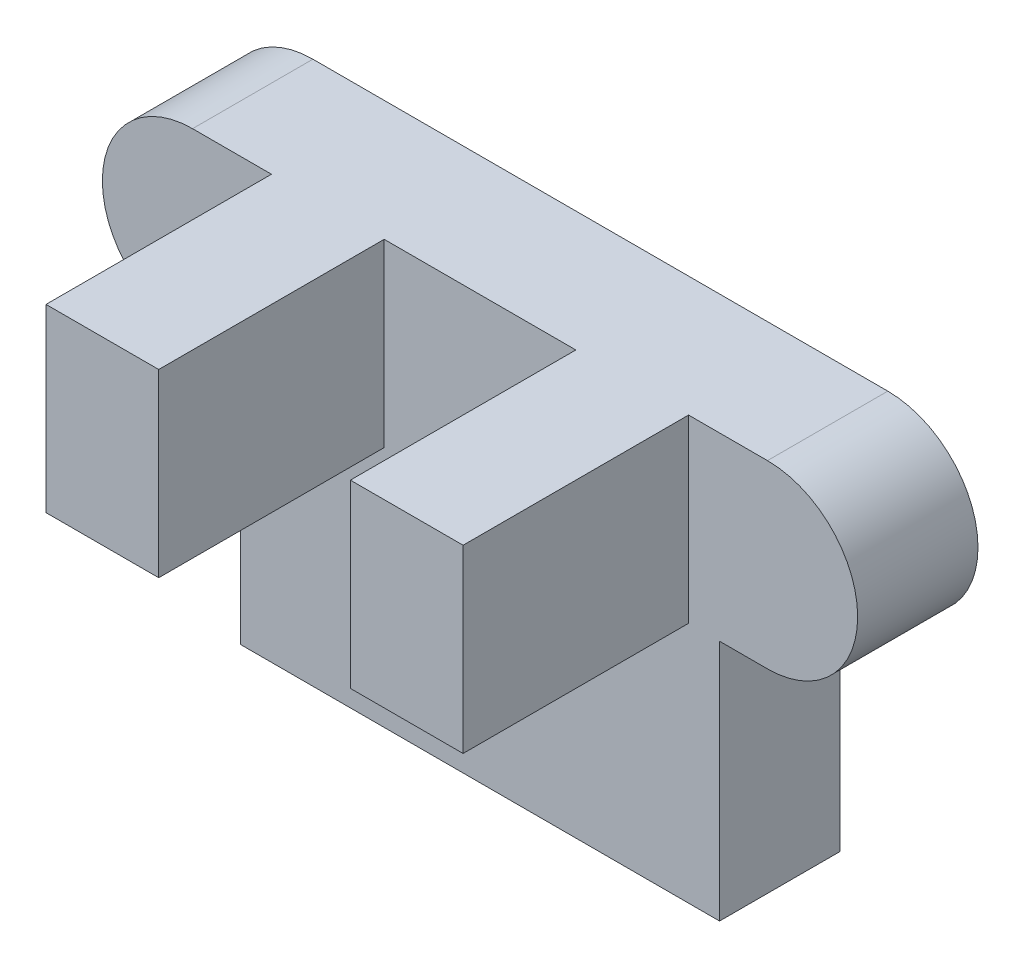
SolidWorks part; units mm, degrees
ref_plane "Front Plane" through (0, 0, 0) normal (0, 0, 1) x (1, 0, 0)
ref_plane "Top Plane" through (0, 0, 0) normal (0, 1, 0) x (1, 0, 0)
ref_plane "Right Plane" through (0, 0, 0) normal (1, 0, 0) x (0, 0, -1)
sketch "Sketch2" plane through (0, 0, 0) normal (0, 0, 1) x (1, 0, 0)
  line L0 (0, 0) -> (20.4, 0) construction
  line L1 (0, 3.2) -> (20.4, 3.2)
  line L2 (0, -3.2) -> (1.7, -3.2)
  line L3 (18.7, -3.2) -> (20.4, -3.2)
  line L5 (1.7, -3.2) -> (1.7, -11.8)
  line L6 (1.7, -11.8) -> (18.7, -11.8)
  line L7 (18.7, -3.2) -> (18.7, -11.8)
  arc A0 (0, 3.2) -> (0, -3.2) centre (0, 0) ccw
  arc A1 (20.4, -3.2) -> (20.4, 3.2) centre (20.4, 0) ccw
  point P3 (10.2, -11.8)
  point P12 (10.2, 3.2)
  point P13 (1.3211, -11.8)
  point P14 (0, 0)
  dimension "D5" = 3.2
  dimension "D1" = 20.4
  dimension "D2" = 6.4
  dimension "D3" = 17
  dimension "D4" = 8.6
extrude "Boss-Extrude1" add sketch "Sketch2" along normal blind 4.27
sketch "Sketch3" plane through (0, 0, 4.27) normal (0, 0, 1) x (1, 0, 0)
  line L0 (20.4, 3.2) -> (0, 3.2) construction
  line L1 (2.8, 3.2) -> (6.8, 3.2)
  line L2 (2.8, 3.2) -> (2.8, -3.2)
  line L3 (2.8, -3.2) -> (6.8, -3.2)
  line L4 (6.8, 3.2) -> (6.8, -3.2)
  line L5 (10.2, 3.2) -> (10.2, -11.8) construction
  line L6 (1.7, -11.8) -> (18.7, -11.8) construction
  line L7 (17.6, -3.2) -> (13.6, -3.2)
  line L8 (13.6, 3.2) -> (13.6, -3.2)
  line L9 (17.6, 3.2) -> (13.6, 3.2)
  line L10 (17.6, 3.2) -> (17.6, -3.2)
  arc A0 (0, 3.2) -> (0, -3.2) centre (0, 0) ccw construction
  point P9 (-3.2, 0)
  dimension "D1" = 4
  dimension "D2" = 6
extrude "Boss-Extrude2" add sketch "Sketch3" along normal blind 8
